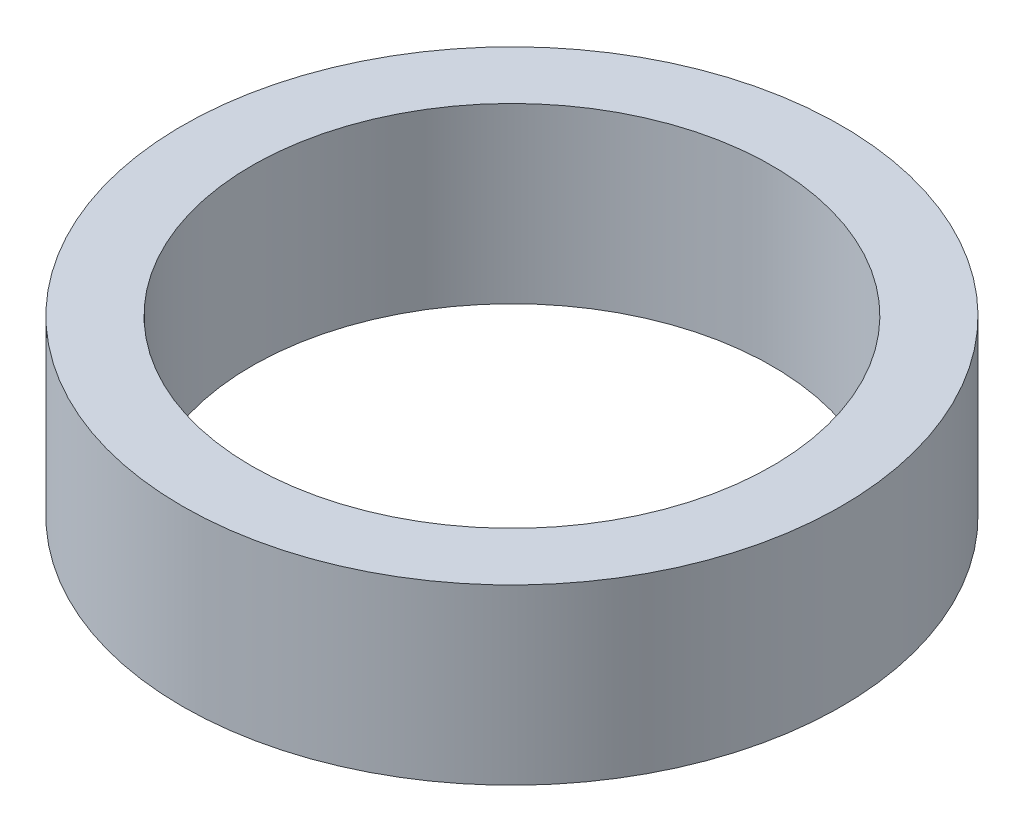
SolidWorks part; units mm, degrees
ref_plane "Front Plane" through (0, 0, 0) normal (0, 0, 1) x (1, 0, 0)
ref_plane "Top Plane" through (0, 0, 0) normal (0, 1, 0) x (1, 0, 0)
ref_plane "Right Plane" through (0, 0, 0) normal (1, 0, 0) x (0, 0, -1)
sketch "Sketch1" plane through (0, 0, 0) normal (0, 1, 0) x (1, 0, 0)
  circle A0 centre (0, 0) radius 19
  circle A1 centre (0, 0) radius 15
extrude "Boss-Extrude1" add sketch "Sketch1" along normal blind 10
